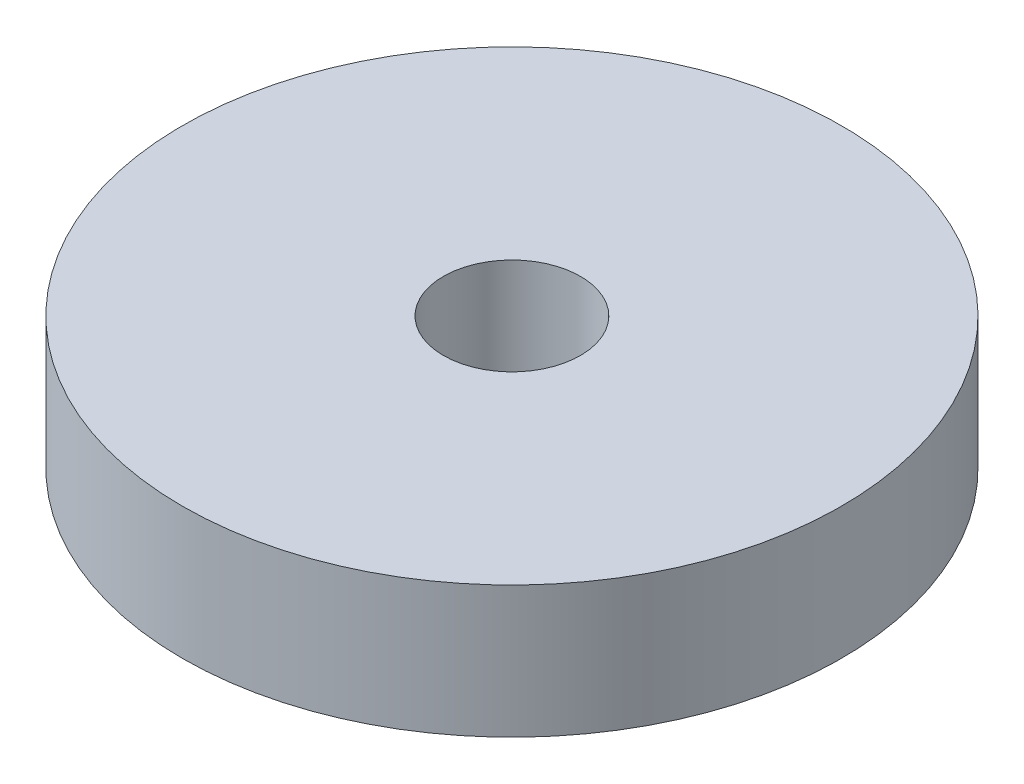
SolidWorks part; units mm, degrees
ref_plane "Front Plane" through (0, 0, 0) normal (0, 0, 1) x (1, 0, 0)
ref_plane "Top Plane" through (0, 0, 0) normal (0, 1, 0) x (1, 0, 0)
ref_plane "Right Plane" through (0, 0, 0) normal (1, 0, 0) x (0, 0, -1)
sketch "Sketch1" plane through (0, 0, 0) normal (0, 1, 0) x (1, 0, 0)
  circle A0 centre (0, 0) radius 12.5
  circle A1 centre (0, 0) radius 2.6
  dimension "D1" = 5.2
  dimension "D2" = 25
extrude "Boss-Extrude1" add sketch "Sketch1" along normal blind 5
